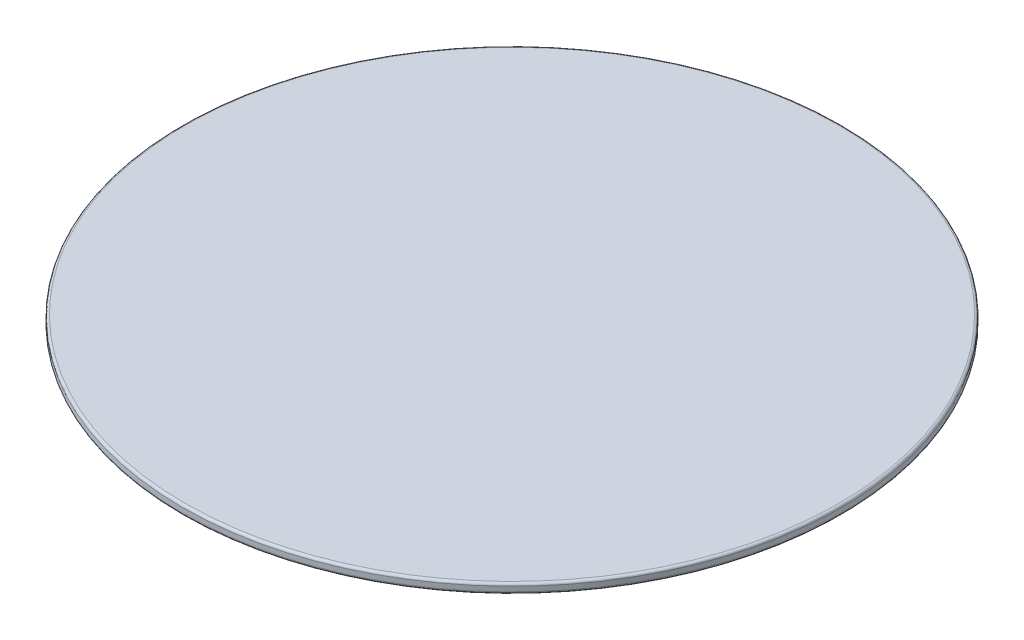
SolidWorks part; units mm, degrees
ref_plane "Front Plane" through (0, 0, 0) normal (0, 0, 1) x (1, 0, 0)
ref_plane "Top Plane" through (0, 0, 0) normal (0, 1, 0) x (1, 0, 0)
ref_plane "Right Plane" through (0, 0, 0) normal (1, 0, 0) x (0, 0, -1)
sketch "Sketch1" plane through (0, 0, 0) normal (0, 1, 0) x (1, 0, 0)
  circle A0 centre (0, 0) radius 135
  dimension "D1" = 270
extrude "Boss-Extrude1" add sketch "Sketch1" along normal blind 4
fillet "Fillet1" radius 1 2 edges at (0, 4, 135) (0, 0, 135)
